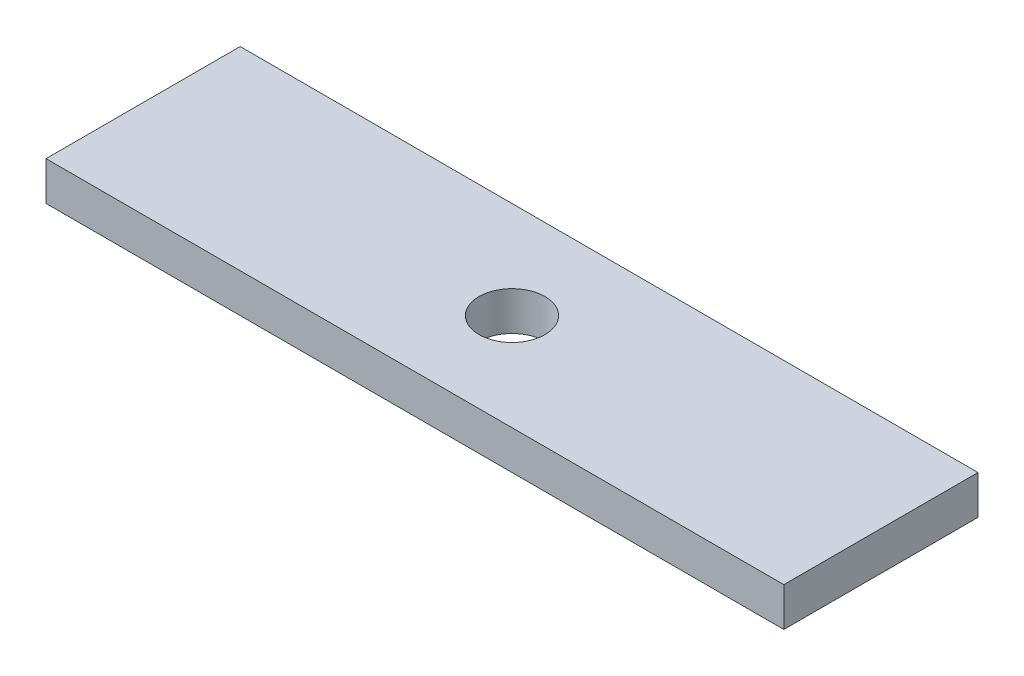
SolidWorks part; units mm, degrees
material "Q235锻制"
ref_plane "前视基准面" through (0, 0, 0) normal (0, 0, 1) x (1, 0, 0)
ref_plane "上视基准面" through (0, 0, 0) normal (0, 1, 0) x (1, 0, 0)
ref_plane "右视基准面" through (0, 0, 0) normal (1, 0, 0) x (0, 0, -1)
sketch "草图1" plane through (0, 0, 0) normal (0, 1, 0) x (1, 0, 0)
  line L1 (-47.5, -12.5) -> (47.5, -12.5)
  line L2 (-47.5, -12.5) -> (-47.5, 12.5)
  line L3 (-47.5, 12.5) -> (47.5, 12.5)
  line L4 (47.5, -12.5) -> (47.5, 12.5)
  line L5 (-47.5, -12.5) -> (47.5, 12.5) construction
  line L6 (-47.5, 12.5) -> (47.5, -12.5) construction
  point P0 (0, 0)
  dimension "D1" = 25
  dimension "D2" = 95
extrude "凸台-拉伸1" add sketch "草图1" along normal blind 5
hole_wizard "M10 螺纹孔1" positions "草图3" profile "草图4" tap size "M10" standard "GB" end condition up to next
sketch "草图3" plane through (0, 0, 0) normal (0, -1, 0) x (-1, 0, 0)
  point P0 (0, 0)
sketch "草图4" plane through (0, 0, 0) normal (1, 0, 0) x (0, 0, -1)
  line L0 (0, 0) -> (0, 5)
  line L1 (0, 5) -> (4.25, 5)
  line L2 (4.25, 5) -> (4.25, 0)
  line L5 (4.25, 0) -> (0, 0)
  line L11 (0, -6.35) -> (0, 107.95) construction
  dimension "通孔螺纹孔钻头直径" = 8.5
  dimension "通孔螺纹孔钻头深度" = 5
cosmetic thread "孔螺纹线1"
